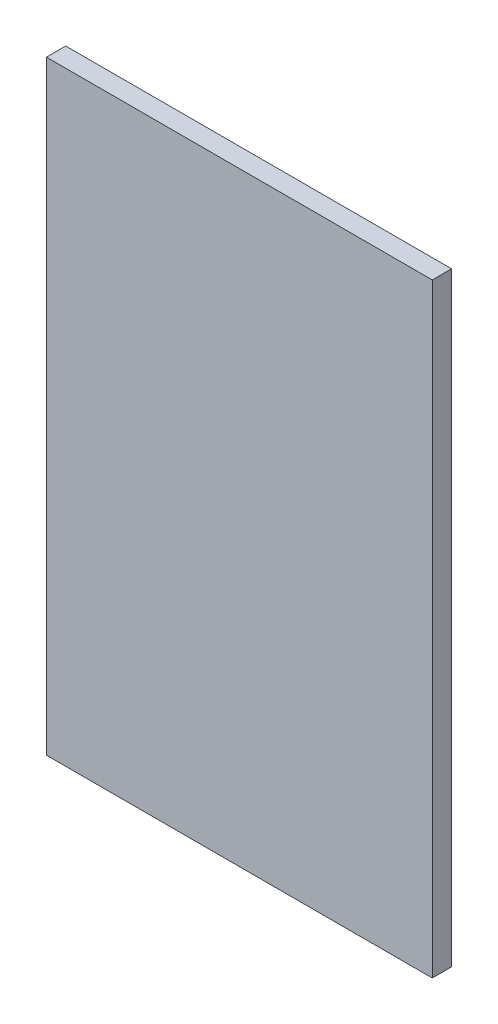
SolidWorks part; units mm, degrees
ref_plane "Alzado" through (0, 0, 0) normal (0, 0, 1) x (1, 0, 0)
ref_plane "Planta" through (0, 0, 0) normal (0, 1, 0) x (1, 0, 0)
ref_plane "Vista lateral" through (0, 0, 0) normal (1, 0, 0) x (0, 0, -1)
sketch "Croquis1" plane through (0, 0, 0) normal (0, 0, 1) x (1, 0, 0)
  line L1 (0, 0) -> (30, 0)
  line L2 (0, 0) -> (0, 47)
  line L3 (0, 47) -> (30, 47)
  line L4 (30, 0) -> (30, 47)
  dimension "D1" = 30
  dimension "D2" = 47
extrude "Saliente-Extruir1" add sketch "Croquis1" along normal blind 1.5
